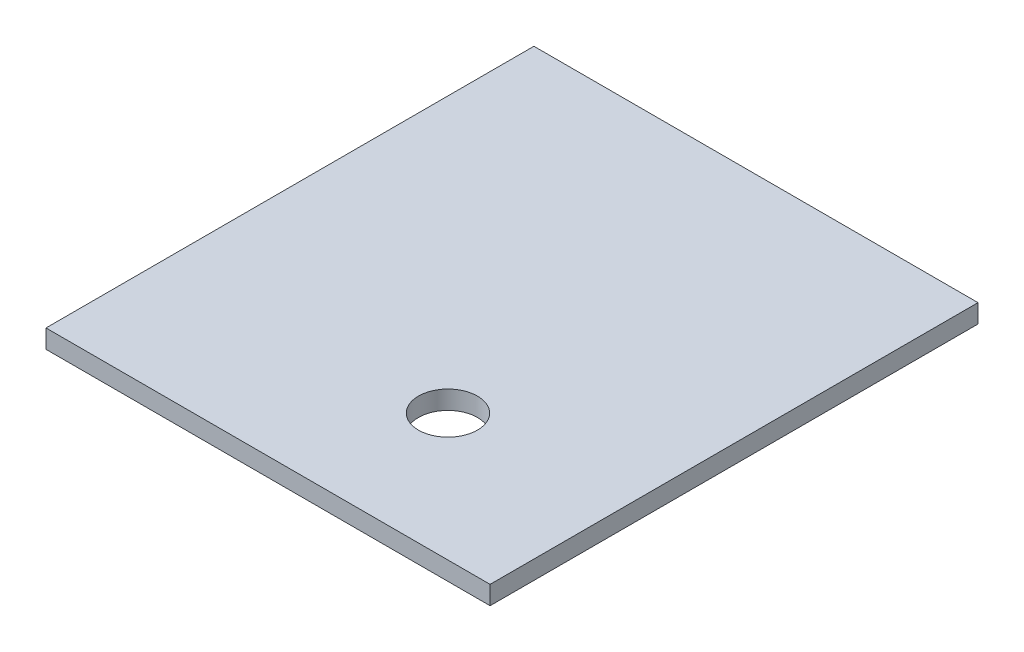
SolidWorks part; units mm, degrees
ref_plane "Front Plane" through (0, 0, 0) normal (0, 0, 1) x (1, 0, 0)
ref_plane "Top Plane" through (0, 0, 0) normal (0, 1, 0) x (1, 0, 0)
ref_plane "Right Plane" through (0, 0, 0) normal (1, 0, 0) x (0, 0, -1)
sketch "Sketch1" plane through (0, 0, 0) normal (0, 1, 0) x (1, 0, 0)
  line L1 (-66.929, -73.533) -> (66.929, -73.533)
  line L2 (-66.929, -73.533) -> (-66.929, 73.533)
  line L3 (-66.929, 73.533) -> (66.929, 73.533)
  line L4 (66.929, -73.533) -> (66.929, 73.533)
  line L5 (-66.929, -73.533) -> (66.929, 73.533) construction
  line L6 (-66.929, 73.533) -> (66.929, -73.533) construction
  point P0 (0, 0)
  dimension "D1" = 133.858
  dimension "D2" = 147.066
extrude "Boss-Extrude1" add sketch "Sketch1" along normal blind 5.588
sketch "Sketch4" plane through (0, 5.588, 0) normal (0, 1, 0) x (1, 0, 0)
  line L0 (-66.929, -73.533) -> (66.929, -73.533) construction
  line L1 (66.929, -73.533) -> (66.929, 73.533) construction
  circle A4 centre (15.875, -35.179) radius 8.89
  dimension "D1" = 17.78
  dimension "D2" = 38.354
  dimension "D3" = 51.054
extrude "Cut-Extrude1" cut sketch "Sketch4" against normal up to next
